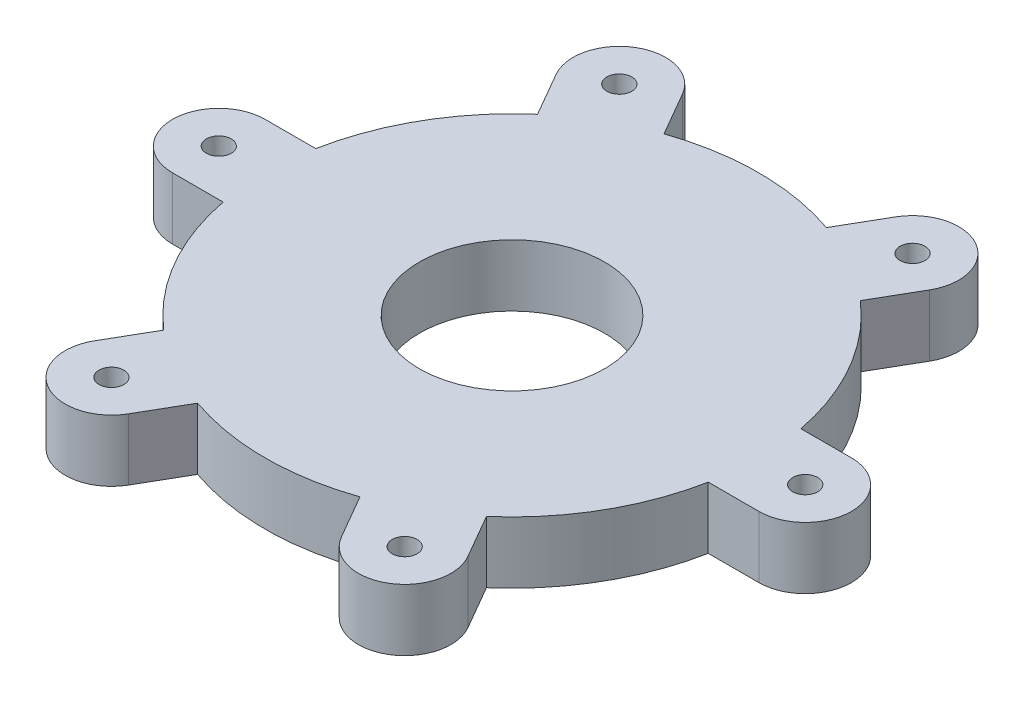
SolidWorks part; units mm, degrees
ref_plane "Front Plane" through (0, 0, 0) normal (0, 0, 1) x (1, 0, 0)
ref_plane "Top Plane" through (0, 0, 0) normal (0, 1, 0) x (1, 0, 0)
ref_plane "Right Plane" through (0, 0, 0) normal (1, 0, 0) x (0, 0, -1)
sketch "Sketch1" plane through (0, 0, 0) normal (0, 1, 0) x (1, 0, 0)
  line L0 (0, 15) -> (0, 25) construction
  circle A0 centre (0, 0) radius 25
  circle A1 centre (0, 0) radius 15
  dimension "D1" = 50
  dimension "D2" = 10
extrude "Boss-Extrude1" add sketch "Sketch1" along normal mid plane 10
sketch "Sketch6" plane through (0, 5, 0) normal (0, 1, 0) x (1, 0, 0)
  circle A0 centre (0, 0) radius 25
  circle A1 centre (0, 0) radius 40
  circle A3 centre (0, 0) radius 25 construction
  dimension "D1" = 80
extrude "Boss-Extrude3" add sketch "Sketch6" against normal blind 10
sketch "Sketch7" plane through (0, -5, 0) normal (0, -1, 0) x (1, 0, 0)
  line L0 (0, 0) -> (21.8172, 16.7409) construction
  line L1 (0, 0) -> (27.5, 0) construction
  circle A0 centre (0, 0) radius 27.5 construction
  circle A1 centre (21.8172, 16.7409) radius 7
  circle A2 centre (-2.5851, 27.3782) radius 7
  circle A3 centre (-24.5651, 12.3615) radius 7
  circle A4 centre (-23.527, -14.2383) radius 7
  circle A5 centre (0, -27.5) radius 7
  circle A6 centre (23.0555, -14.9897) radius 7
  point P3 (21.8172, 16.7409)
  point P4 (-2.5851, 27.3782)
  point P5 (-24.5651, 12.3615)
  point P6 (-23.527, -14.2383)
  point P7 (-0.4436, -27.4964)
  point P8 (23.0555, -14.9897)
  dimension "D1" = 55
  dimension "D8" = 14
  dimension "D2" = 26.62
  dimension "D3" = 26.62
  dimension "D4" = 26.62
  dimension "D5" = 26.62
  dimension "D6" = 37.5
  dimension "D7" = 26.62
extrude "Cut-Extrude1" cut sketch "Sketch7" against normal blind 5
sketch "Sketch8" plane through (0, 5, 0) normal (0, 1, 0) x (1, 0, 0)
  line L0 (47.5, 7.5) -> (39.2906, 7.5)
  line L2 (39.2906, -7.5) -> (47.5, -7.5)
  line L3 (39.2906, -7.5) -> (39.2906, 7.5)
  circle A0 centre (0, 0) radius 55 construction
  arc A1 (47.5, -7.5) -> (47.5, 7.5) centre (47.5, 0) ccw
  circle A3 centre (0, 0) radius 40 construction
  dimension "D1" = 110
  dimension "D2" = 15
extrude "Boss-Extrude4" add sketch "Sketch8" against normal up to surface (10 mm away) up to face at (23.0555, -5, -21.9897)
sketch "Sketch10" plane through (0, 5, 0) normal (0, 1, 0) x (1, 0, 0)
  circle A0 centre (0, 0) radius 47.5 construction
  point P3 (47.5, 0)
  dimension "D1" = 95
hole_wizard "Tap Drill for #10-32 Tap1" positions "Sketch11" profile "Sketch12" hole size "#10-32" standard "ANSI Inch" end condition up to next
sketch "Sketch11" plane through (0, 5, 0) normal (0, 1, 0) x (1, 0, 0)
  point P0 (47.5, 0)
sketch "Sketch12" plane through (47.5, 5, 0) normal (1, 0, 0) x (0, 0, 1)
  line L0 (0, 0) -> (0, 10)
  line L1 (0, 10) -> (2.0193, 10)
  line L2 (2.0193, 10) -> (2.0193, 0)
  line L5 (2.0193, 0) -> (0, 0)
  line L11 (0, -6.35) -> (0, 107.95) construction
  dimension "Thru Hole Dia." = 4.0386
  dimension "Thru Hole Depth" = 10
pattern_circular "CirPattern1" count 6 over 360 about axis through (0, 0, 0) along (0, 1, 0) of "Tap Drill for #10-32 Tap1", "Boss-Extrude4"
equation "\"GEARDIST\"=26.62"
equation "\"D2@Sketch7\"=\"GEARDIST\""
equation "\"D3@Sketch7\"=\"GEARDIST\""
equation "\"D4@Sketch7\"=\"GEARDIST\""
equation "\"D5@Sketch7\"=\"GEARDIST\""
equation "\"D7@Sketch7\"=\"GEARDIST\""
